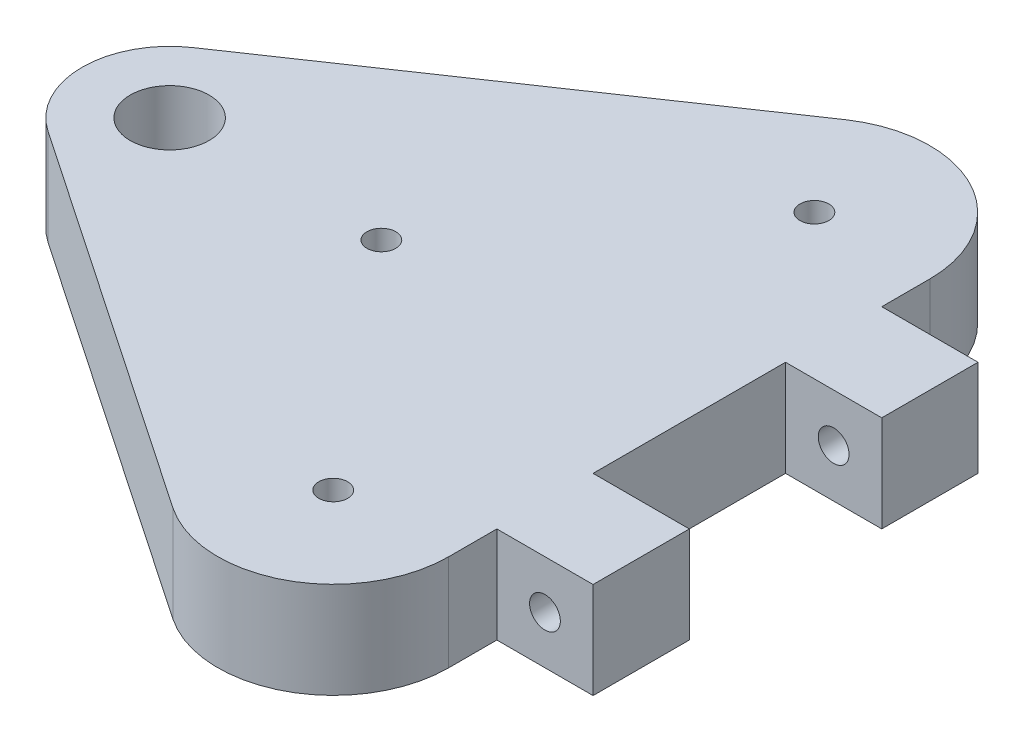
SolidWorks part; units mm, degrees
ref_plane "正面" through (0, 0, 0) normal (0, 0, 1) x (1, 0, 0)
ref_plane "平面" through (0, 0, 0) normal (0, 1, 0) x (1, 0, 0)
ref_plane "右側面" through (0, 0, 0) normal (1, 0, 0) x (0, 0, -1)
sketch "ｽｹｯﾁ1" plane through (0, 0, 0) normal (0, 1, 0) x (1, 0, 0)
  line L0 (-47.1103, 7.5296) -> (-6.7388, 34.9292)
  line L1 (12, 25) -> (12, -25)
  line L2 (-6.7388, -34.9292) -> (-47.1103, -7.5296)
  circle A2 centre (-42, 0) radius 4.1
  arc A3 (12, 25) -> (-6.7388, 34.9292) centre (0, 25) ccw
  arc A4 (-6.7388, -34.9292) -> (12, -25) centre (0, -25) ccw
  arc A5 (-47.1103, 7.5296) -> (-47.1103, -7.5296) centre (-42, 0) ccw
  dimension "D1" = 8.2
  dimension "D2" = 12
  dimension "D5" = 42
  dimension "D6" = 25
  dimension "D8" = 5
  dimension "D4" = 12
  dimension "D3" = 25
extrude "ﾎﾞｽ - 押し出し1" add sketch "ｽｹｯﾁ1" along normal blind 10
sketch "ｽｹｯﾁ2" plane through (0, 0, 0) normal (0, -1, 0) x (1, 0, 0)
  line L1 (-5.1, 19.9) -> (5.1, 19.9)
  line L2 (-5.1, 19.9) -> (-5.1, 30.1)
  line L3 (-5.1, 30.1) -> (5.1, 30.1)
  line L4 (5.1, 19.9) -> (5.1, 30.1)
  line L5 (-5.1, 19.9) -> (5.1, 30.1) construction
  line L6 (-5.1, 30.1) -> (5.1, 19.9) construction
  line L7 (-5.1, -19.9) -> (5.1, -19.9)
  line L8 (-5.1, -19.9) -> (-5.1, -30.1)
  line L9 (-5.1, -30.1) -> (5.1, -30.1)
  line L10 (5.1, -19.9) -> (5.1, -30.1)
  line L11 (-5.1, -19.9) -> (5.1, -30.1) construction
  line L12 (-5.1, -30.1) -> (5.1, -19.9) construction
  line L13 (-25.1, -5.1) -> (-14.9, -5.1)
  line L14 (-25.1, -5.1) -> (-25.1, 5.1)
  line L15 (-25.1, 5.1) -> (-14.9, 5.1)
  line L16 (-14.9, -5.1) -> (-14.9, 5.1)
  line L17 (-25.1, -5.1) -> (-14.9, 5.1) construction
  line L18 (-25.1, 5.1) -> (-14.9, -5.1) construction
  point P0 (0, 25)
  point P5 (0, -25)
  point P10 (-20, 0)
  dimension "D1" = 10.2
  dimension "D2" = 25
  dimension "D3" = 25
  dimension "D4" = 20
extrude "ｶｯﾄ - 押し出し1" cut sketch "ｽｹｯﾁ2" against normal blind 5
sketch "ｽｹｯﾁ3" plane through (12, 0, 0) normal (1, 0, 0) x (0, 0, -1)
  line L0 (-25, 10) -> (25, 10) construction
  line L1 (-20, 10) -> (-10, 10)
  line L2 (-20, 10) -> (-20, 0)
  line L3 (-20, 0) -> (-10, 0)
  line L4 (-10, 10) -> (-10, 0)
  line L5 (-20, 10) -> (-10, 0) construction
  line L6 (-20, 0) -> (-10, 10) construction
  line L7 (-25, 0) -> (25, 0) construction
  line L9 (10, 10) -> (20, 10)
  line L10 (10, 10) -> (10, 0)
  line L11 (10, 0) -> (20, 0)
  line L12 (20, 10) -> (20, 0)
  line L13 (10, 10) -> (20, 0) construction
  line L14 (10, 0) -> (20, 10) construction
  point P4 (-15, 5)
  point P13 (15, 5)
  dimension "D1" = 15
  dimension "D2" = 15
extrude "ﾎﾞｽ - 押し出し2" add sketch "ｽｹｯﾁ3" along normal blind 10
sketch "ｽｹｯﾁ4" plane through (0, 0, 0) normal (0, 0, 1) x (1, 0, 0)
  line L0 (22, 10) -> (22, 0) construction
  line L1 (22, 10) -> (12, 10) construction
  circle A0 centre (17, 5) radius 1.6
  point P4 (22, 5)
  point P7 (17, 10)
  dimension "D1" = 3.2
extrude "ｶｯﾄ - 押し出し2" cut sketch "ｽｹｯﾁ4" against normal through all both and the other way through all
sketch "ｽｹｯﾁ5" plane through (0, 0, 0) normal (0, 1, 0) x (1, 0, 0)
  line L0 (-5.1, -30.1) -> (5.1, -19.9) construction
  line L1 (-5.1, -19.9) -> (5.1, -30.1) construction
  line L2 (-25.1, -5.1) -> (-14.9, 5.1) construction
  line L3 (-25.1, 5.1) -> (-14.9, -5.1) construction
  line L4 (-5.1, 19.9) -> (5.1, 30.1) construction
  line L5 (-5.1, 30.1) -> (5.1, 19.9) construction
  circle A0 centre (0, -25) radius 1.5
  circle A1 centre (-20, 0) radius 1.5
  circle A2 centre (0, 25) radius 1.5
  dimension "D1" = 3
extrude "ｶｯﾄ - 押し出し3" cut sketch "ｽｹｯﾁ5" along normal through all
